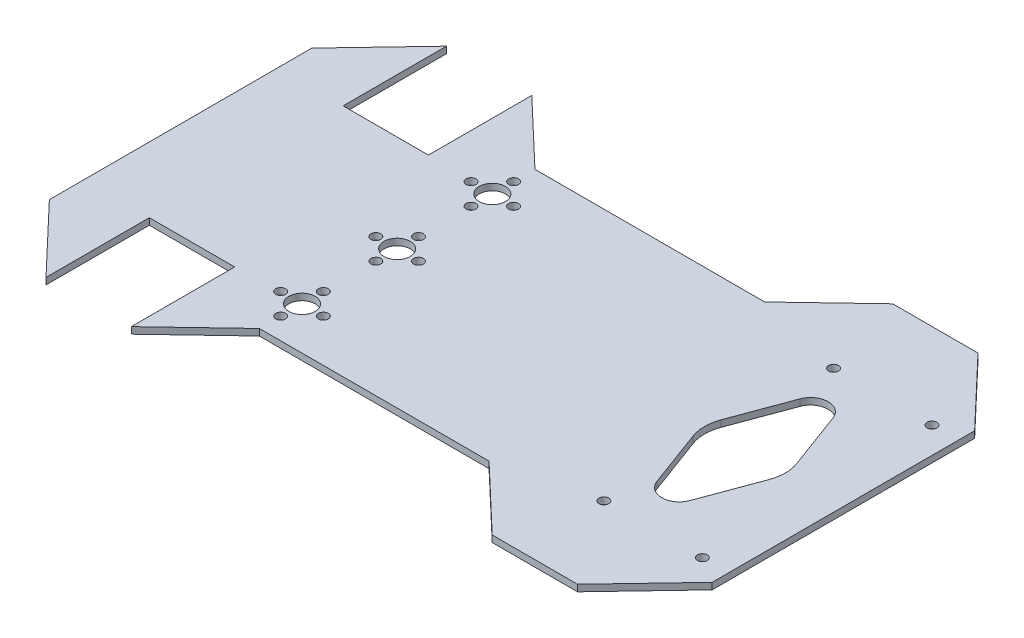
SolidWorks part; units mm, degrees
ref_plane "Front Plane" through (0, 0, 0) normal (0, 0, 1) x (1, 0, 0)
ref_plane "Top Plane" through (0, 0, 0) normal (0, 1, 0) x (1, 0, 0)
ref_plane "Right Plane" through (0, 0, 0) normal (1, 0, 0) x (0, 0, -1)
sketch "Sketch1" plane through (0, 0, 0) normal (0, 1, 0) x (1, 0, 0)
  line L0 (-101, 0) -> (101, 0) construction
  line L13 (-55, 61.025) -> (-35, 42)
  line L20 (-81, 61.025) -> (-55, 61.025)
  line L21 (-101, 40) -> (-81, 61.025)
  line L22 (-101, 40) -> (-101, -40)
  line L23 (-35, 42) -> (35, 42)
  line L24 (0, 42) -> (0, -42) construction
  line L25 (81, 61.025) -> (55, 61.025)
  line L26 (55, 61.025) -> (35, 42)
  line L27 (101, 40) -> (101, -40)
  line L28 (101, 40) -> (81, 61.025)
  line L37 (55, -61.025) -> (35, -42)
  line L38 (81, -61.025) -> (55, -61.025)
  line L39 (101, -40) -> (81, -61.025)
  line L40 (-81, -61.025) -> (-55, -61.025)
  line L41 (-55, -61.025) -> (-35, -42)
  line L42 (-101, -40) -> (-81, -61.025)
  line L46 (-35, -42) -> (35, -42)
  point P0 (0, 0)
  point P16 (0, 0)
  dimension "D1" = 20
  dimension "D2" = 84
  dimension "D3" = 40
  dimension "D4" = 35
  dimension "D5" = 26
  dimension "D6" = 202
extrude "Boss-Extrude1" add sketch "Sketch1" along normal blind 2
sketch "Sketch2" plane through (0, 2, 0) normal (0, 1, 0) x (1, 0, 0)
  line L0 (-101, 0) -> (101, 0) construction
  line L1 (-101, 40) -> (-101, -40) construction
  line L2 (101, -40) -> (101, 40) construction
sketch "Sketch4" plane through (0, 2, 0) normal (0, 1, 0) x (1, 0, 0)
  line L0 (76.0166, 21.8591) -> (82.5335, 4.2742)
  line L4 (101, -40) -> (101, 40) construction
  line L6 (59.4665, 4.2742) -> (65.9834, 21.8591)
  line L7 (76.0166, -21.8591) -> (82.5335, -4.2743)
  line L8 (59.4665, -4.2743) -> (65.9834, -21.8591)
  line L9 (101, 0) -> (4.215, 0) construction
  arc A4 (76.0166, 21.8591) -> (65.9834, 21.8591) centre (71, 20) ccw
  arc A5 (65.9834, -21.8591) -> (76.0166, -21.8591) centre (71, -20) ccw
  arc A6 (59.4665, 4.2742) -> (59.4665, -4.2743) centre (71, 0) ccw
  arc A8 (82.5335, -4.2743) -> (82.5335, 4.2742) centre (71, 0) ccw
  dimension "D1" = 24.6
  dimension "D2" = 20
  dimension "D3" = 20
  dimension "D4" = 30
  dimension "D6" = 10.7
  dimension "D7" = 10.7
sketch "Sketch5" plane through (0, 0, 0) normal (0, -1, 0) x (1, 0, 0)
  line L0 (-101, 0) -> (101, 0) construction
  line L5 (-81, -61.025) -> (-55, -61.025)
  line L6 (-81, -61.025) -> (-81, -29.525)
  line L8 (-81, -29.525) -> (-55, -29.525)
  line L9 (-55, -61.025) -> (-55, -29.525)
  line L10 (-81, 29.525) -> (-55, 29.525)
  line L11 (-55, 61.025) -> (-55, 29.525)
  line L12 (-81, 61.025) -> (-55, 61.025)
  line L13 (-81, 61.025) -> (-81, 29.525)
  dimension "D1" = 26
  dimension "D2" = 31.5
extrude "Cut-Extrude3" cut sketch "Sketch5" against normal through all
extrude "Cut-Extrude4" cut sketch "Sketch4" against normal through all
sketch "Sketch8" plane through (0, 2, 0) normal (0, 1, 0) x (1, 0, 0)
  line L2 (0, -42) -> (0, 42) construction
  line L3 (-35, -42) -> (35, -42) construction
  line L4 (35, 42) -> (-35, 42) construction
  line L5 (0, 0) -> (-101, 0) construction
  line L6 (-101, 40) -> (-101, -40) construction
  circle A0 centre (-35, -22.5) radius 1.5
  circle A1 centre (-41.5, -29) radius 1.5
  circle A2 centre (-35, -35.5) radius 1.5
  circle A3 centre (-28.5, -29) radius 1.5
  circle A8 centre (-35, -29) radius 4
  circle A9 centre (-35, 29) radius 4
  circle A10 centre (-28.5, 29) radius 1.5
  circle A11 centre (-35, 35.5) radius 1.5
  circle A12 centre (-41.5, 29) radius 1.5
  circle A13 centre (-35, 22.5) radius 1.5
  circle A14 centre (-35, 0) radius 4
  circle A15 centre (-35, 6.5) radius 1.5
  circle A16 centre (-28.5, 0) radius 1.5
  circle A17 centre (-41.5, 0) radius 1.5
  circle A18 centre (-35, -6.5) radius 1.5
  point P41 (0, 0)
  point P42 (0, 0)
  point P43 (0, 0)
  dimension "D1" = 3
  dimension "D2" = 3
  dimension "D3" = 3
  dimension "D4" = 3
  dimension "D5" = 58
  dimension "D6" = 3
  dimension "D7" = 3
  dimension "D8" = 3
  dimension "D9" = 6.5
  dimension "D10" = 6.5
  dimension "D11" = 6.5
  dimension "D12" = 35
  dimension "D13" = 6.5
  dimension "D14" = 8
  dimension "D15" = 3
  dimension "D16" = 6.5
  dimension "D17" = 6.5
  dimension "D18" = 8
extrude "Cut-Extrude5" cut sketch "Sketch8" against normal through all
sketch "Sketch9" plane through (0, 2, 0) normal (0, 1, 0) x (1, 0, 0)
  line L1 (83.3, 0) -> (101, 0) construction
  line L2 (101, -40) -> (101, 40) construction
  circle A1 centre (93, 35) radius 1.5
  circle A2 centre (63, 35) radius 1.5
  arc A4 (82.5335, -4.2743) -> (82.5335, 4.2742) centre (71, 0) ccw construction
  circle A5 centre (63, -35) radius 1.5
  circle A6 centre (93, -35) radius 1.5
  dimension "D1" = 70
  dimension "D2" = 3
  dimension "D3" = 3
  dimension "D4" = 8
  dimension "D5" = 30
extrude "Cut-Extrude6" cut sketch "Sketch9" against normal through all
